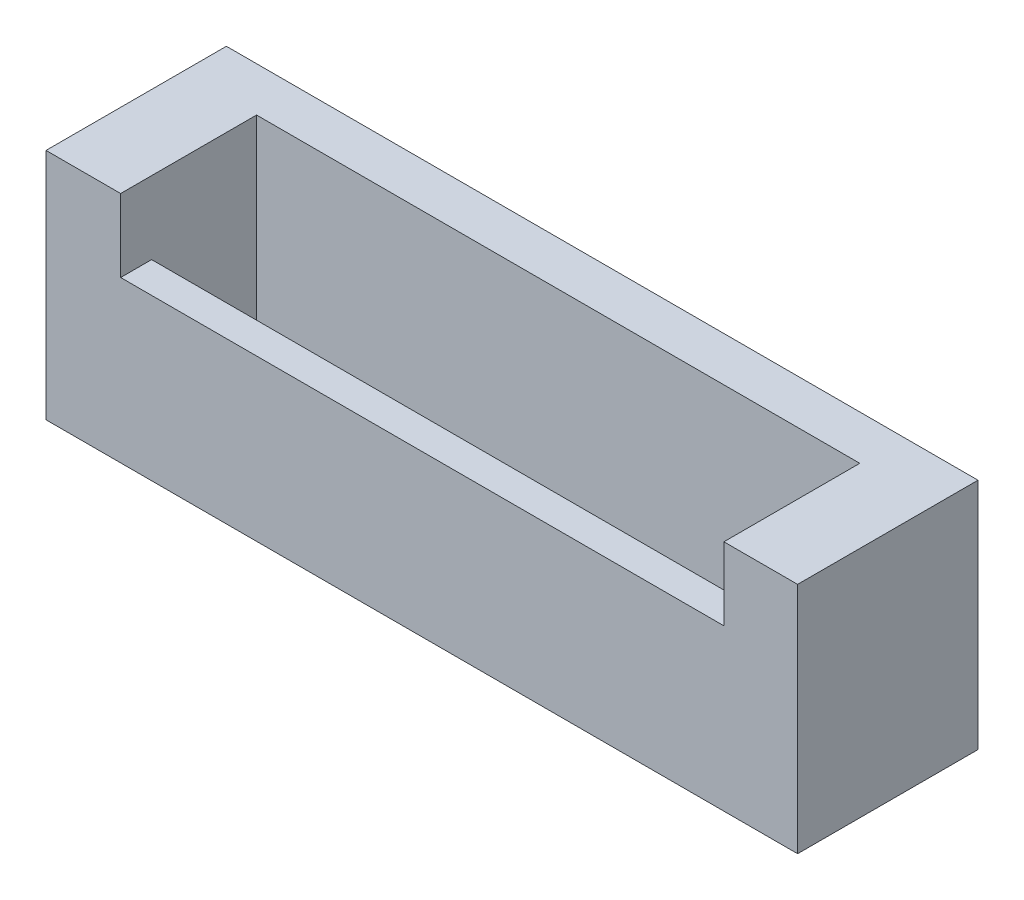
SolidWorks part; units mm, degrees
ref_plane "Front Plane" through (0, 0, 0) normal (0, 0, 1) x (1, 0, 0)
ref_plane "Top Plane" through (0, 0, 0) normal (0, 1, 0) x (1, 0, 0)
ref_plane "Right Plane" through (0, 0, 0) normal (1, 0, 0) x (0, 0, -1)
sketch "Sketch1" plane through (0, 0, 0) normal (0, 1, 0) x (1, 0, 0)
  line L1 (0, 0) -> (-50, 0)
  line L2 (0, 0) -> (0, -12)
  line L3 (0, -12) -> (-50, -12)
  line L4 (-50, 0) -> (-50, -12)
  dimension "D1" = 12
  dimension "D2" = 50
extrude "Boss-Extrude1" add sketch "Sketch1" along normal blind 15.52
sketch "Sketch2" plane through (0, 15.52, 0) normal (0, 1, 0) x (1, 0, 0)
  line L1 (-45.0346, -2.9582) -> (-4.9046, -2.9582)
  line L2 (-45.0346, -2.9582) -> (-45.0346, -9.9382)
  line L3 (-45.0346, -9.9382) -> (-4.9046, -9.9382)
  line L4 (-4.9046, -2.9582) -> (-4.9046, -9.9382)
  dimension "D1" = 6.98
  dimension "D2" = 40.13
extrude "Cut-Extrude1" cut sketch "Sketch2" against normal blind 15
sketch "Sketch3" plane through (0, 15.52, 0) normal (0, 1, 0) x (1, 0, 0)
  line L0 (-50, -12) -> (0, -12) construction
  line L1 (-4.9046, -9.9382) -> (-45.0346, -9.9382)
  line L2 (-4.9046, -9.9382) -> (-4.9046, -12)
  line L3 (-4.9046, -12) -> (-45.0346, -12)
  line L4 (-45.0346, -9.9382) -> (-45.0346, -12)
  line L5 (-45.0346, -2.9582) -> (-45.0346, -9.9382) construction
  line L7 (-4.9046, -9.9382) -> (-4.9046, -2.9582) construction
extrude "Cut-Extrude2" cut sketch "Sketch3" against normal offset from surface (4.84 mm away) 10.16 up to face at (-24.9696, 0.52, 6.4482)
